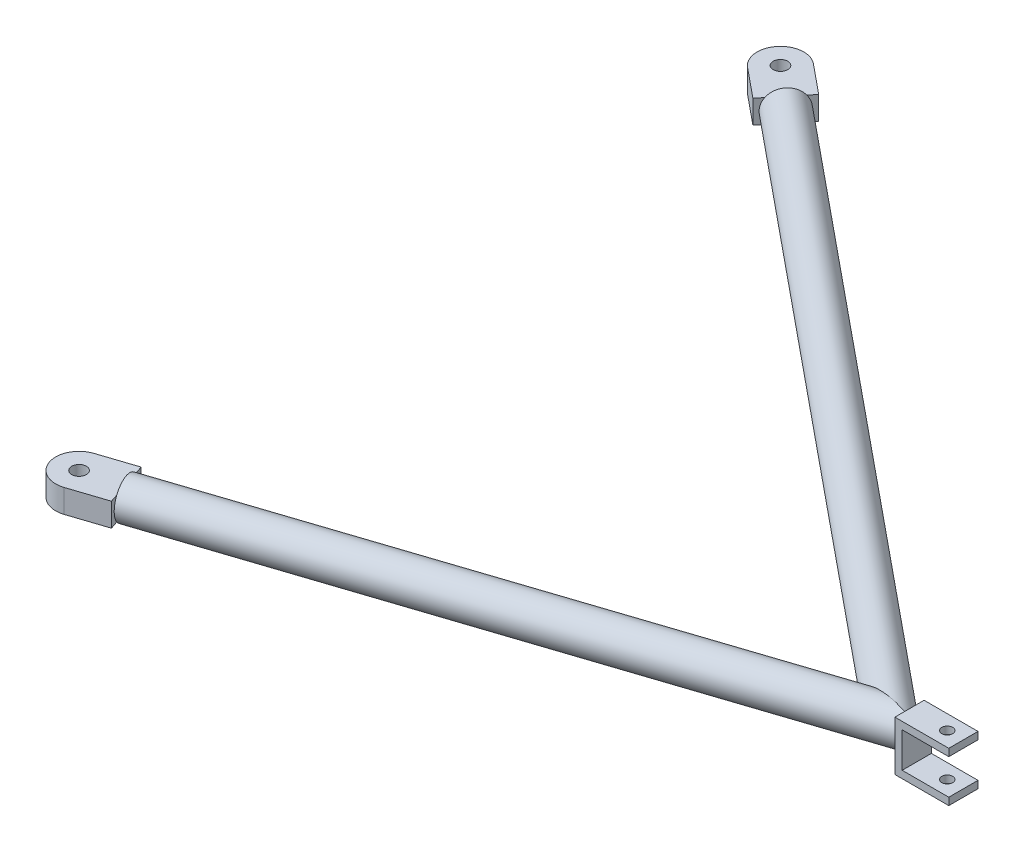
SolidWorks part; units mm, degrees
ref_plane "Front Plane" through (0, 0, 0) normal (0, 0, 1) x (1, 0, 0)
ref_plane "Top Plane" through (0, 0, 0) normal (0, 1, 0) x (1, 0, 0)
ref_plane "Right Plane" through (0, 0, 0) normal (1, 0, 0) x (0, 0, -1)
sketch "Sketch1" plane through (0, 0, 0) normal (0, 1, 0) x (1, 0, 0)
  line L0 (-265.3198, -87.5771) -> (0, 0)
  line L1 (0, 0) -> (-265.3198, 217.2229)
  line L2 (-265.3198, 217.2229) -> (-265.3198, -87.5771) construction
  dimension "D1" = 279.4
  dimension "D2" = 342.9
  dimension "D3" = 304.8
ref_plane "Plane1" through (-265.3198, 0, 87.5771) normal (0.9496, 0, -0.3134) x (-0.3134, 0, -0.9496)
sketch "Sketch2" plane through (-265.3198, 0, 87.5771) normal (0.9496, 0, -0.3134) x (-0.3134, 0, -0.9496)
  circle A0 centre (0, 0) radius 8.255
  dimension "D1" = 16.51
sweep "Sweep1" add profiles "Sketch2" path "Sketch1"
sketch "Sketch3" plane through (0, 0, 0) normal (0, 0, 1) x (1, 0, 0)
  line L0 (33.9318, 10.795) -> (10.504, 10.795)
  line L1 (10.504, 10.795) -> (10.504, -10.795)
  line L2 (10.504, -10.795) -> (33.9318, -10.795)
  line L3 (33.9318, -10.795) -> (33.9318, -7.62)
  line L4 (33.9318, -7.62) -> (13.679, -7.62)
  line L5 (13.679, -7.62) -> (13.679, 7.62)
  line L6 (13.679, 7.62) -> (33.9318, 7.62)
  line L7 (33.9318, 7.62) -> (33.9318, 10.795)
  line L8 (16.854, 0) -> (-16.854, 0) construction
  ellipse E0 centre (0, 0) end of major axis (16.854, 0) minor radius 8.255 construction
  ellipse E1 centre (0, 0) end of major axis (16.854, 0) minor radius 8.255 construction
  point P21 (10.504, 0)
  dimension "D1" = 3.175
  dimension "D2" = 15.24
  dimension "D3" = 3.175
  dimension "D4" = 6.35
extrude "Boss-Extrude1" add sketch "Sketch3" along normal blind 8.89 and the other way blind 3.81
sketch "Sketch4" plane through (-265.3198, 0, 87.5771) normal (-0.9496, 0, 0.3134) x (0.3134, 0, 0.9496)
  line L1 (-10.16, 5.08) -> (10.16, 5.08)
  line L2 (-10.16, 5.08) -> (-10.16, -5.08)
  line L3 (-10.16, -5.08) -> (10.16, -5.08)
  line L4 (10.16, 5.08) -> (10.16, -5.08)
  line L5 (-10.16, 5.08) -> (10.16, -5.08) construction
  line L6 (-10.16, -5.08) -> (10.16, 5.08) construction
  circle A1 centre (0, 0) radius 8.255
  circle A2 centre (0, 0) radius 8.255 construction
  dimension "D2" = 20.32
  dimension "D3" = 10.16
  dimension "D1" = 0
extrude "Boss-Extrude2" add sketch "Sketch4" along normal blind 10.16 and the other way blind 16.256
sketch "Sketch5" plane through (-265.3198, 0, -217.2229) normal (-0.7738, 0, -0.6335) x (-0.6335, 0, 0.7738)
  line L1 (-10.16, 5.08) -> (10.16, 5.08)
  line L2 (-10.16, 5.08) -> (-10.16, -5.08)
  line L3 (-10.16, -5.08) -> (10.16, -5.08)
  line L4 (10.16, 5.08) -> (10.16, -5.08)
  line L5 (-10.16, 5.08) -> (10.16, -5.08) construction
  line L6 (-10.16, -5.08) -> (10.16, 5.08) construction
  point P0 (0, 0)
  dimension "D1" = 20.32
  dimension "D2" = 10.16
extrude "Boss-Extrude3" add sketch "Sketch5" along normal blind 10.16 and the other way blind 16.51
sketch "Sketch6" plane through (0, 5.08, 0) normal (0, 1, 0) x (1, 0, 0)
  line L0 (-246.1089, 214.6254) -> (-266.7449, 231.5205) construction
  line L1 (-258.9814, 198.9027) -> (-279.6174, 215.7978) construction
  line L2 (-279.6174, 215.7978) -> (-266.7449, 231.5205) construction
  line L3 (-271.7561, 209.3616) -> (-279.6174, 215.7978)
  line L4 (-279.6174, 215.7978) -> (-273.1812, 223.6592)
  arc A0 (-273.1812, 223.6592) -> (-271.7561, 209.3616) centre (-265.3198, 217.2229) ccw
extrude "Cut-Extrude1" cut sketch "Sketch6" against normal through all
ref_plane "Plane2" through (0, 0, 0) normal (-0.6335, 0, 0.7738) x (0.7738, 0, 0.6335)
ref_plane "Plane3" through (0, 0, 0) normal (0.3134, 0, 0.9496) x (0.9496, 0, -0.3134)
mirror "Mirror1" about plane through (0, 0, 0) normal (-0.6335, 0, 0.7738) of "Cut-Extrude1"
sketch "Sketch7" plane through (0, 5.08, 0) normal (0, 1, 0) x (1, 0, 0)
  line L0 (-246.6984, -92.1297) -> (-271.7832, -100.4097) construction
  line L1 (-253.0677, -72.8337) -> (-278.1524, -81.1137) construction
  line L2 (-271.7832, -100.4097) -> (-278.1524, -81.1137) construction
  line L3 (-262.1352, -97.2251) -> (-271.7832, -100.4097)
  line L4 (-271.7832, -100.4097) -> (-274.9678, -90.7617)
  arc A0 (-262.1352, -97.2251) -> (-274.9678, -90.7617) centre (-265.3198, -87.5771) cw
extrude "Cut-Extrude2" cut sketch "Sketch7" against normal through all
mirror "Mirror2" about plane through (0, 0, 0) normal (0.3134, 0, 0.9496) of "Cut-Extrude2"
sketch "Sketch8" plane through (-265.3198, 0, 87.5771) normal (-0.9496, 0, 0.3134) x (0.3134, 0, 0.9496)
  line L0 (6.5068, -5.08) -> (-6.5068, -5.08) construction
  line L1 (-6.5068, 5.08) -> (6.5068, 5.08) construction
  line L2 (6.5068, -5.08) -> (-6.5068, -5.08)
  line L3 (-6.5068, 5.08) -> (6.5068, 5.08)
  arc A0 (-6.5068, -5.08) -> (6.5068, -5.08) centre (0, 0) ccw construction
  arc A1 (6.5068, 5.08) -> (-6.5068, 5.08) centre (0, 0) ccw construction
  arc A2 (-6.5068, -5.08) -> (6.5068, -5.08) centre (0, 0) ccw
  arc A3 (6.5068, 5.08) -> (-6.5068, 5.08) centre (0, 0) ccw
extrude "Cut-Extrude3" cut sketch "Sketch8" against normal up to surface (16.256 mm away) up to face at (-247.134, 0, 90.8102)
sketch "Sketch9" plane through (-265.3198, 0, -217.2229) normal (-0.7738, 0, -0.6335) x (-0.6335, 0, 0.7738)
  line L0 (6.5068, -5.08) -> (-6.5068, -5.08) construction
  line L1 (-6.5068, 5.08) -> (6.5068, 5.08) construction
  line L2 (6.5068, -5.08) -> (-6.5068, -5.08)
  line L3 (-6.5068, 5.08) -> (6.5068, 5.08)
  arc A0 (-6.5068, -5.08) -> (6.5068, -5.08) centre (0, 0) ccw construction
  arc A1 (6.5068, 5.08) -> (-6.5068, 5.08) centre (0, 0) ccw construction
  arc A2 (-6.5068, -5.08) -> (6.5068, -5.08) centre (0, 0) ccw
  arc A3 (6.5068, 5.08) -> (-6.5068, 5.08) centre (0, 0) ccw
extrude "Cut-Extrude4" cut sketch "Sketch9" against normal up to surface (16.51 mm away) up to face at (-258.1011, 0, -199.9779)
sketch "Sketch10" plane through (0, 5.08, 0) normal (0, 1, 0) x (1, 0, 0)
  point P0 (-265.3198, 217.2229)
  point P1 (-265.3198, -87.5771)
hole_wizard "E (0.25) Diameter Hole1" positions "3DSketch1" profile "Sketch11" hole size "E" standard "ANSI Inch"
sketch3d "3DSketch1"
  point P0 (-265.3198, 5.08, -217.2229)
  point P3 (-265.3198, 5.08, 87.5771)
sketch "Sketch11" plane through (-265.3198, 5.08, -217.2229) normal (1, 0, 0) x (0, 0, 1)
  line L0 (0, 0) -> (0, 20.9577)
  line L1 (0, 20.9577) -> (3.175, 19.05)
  line L2 (3.175, 19.05) -> (3.175, 0)
  line L5 (3.175, 0) -> (0, 0)
  line L10 (0, 20.9577) -> (-3.175, 19.05) construction
  line L11 (0, -6.35) -> (0, 107.95) construction
  dimension "Hole Dia." = 6.35
  dimension "Hole Depth" = 19.05
  dimension "Drill Angle" = 118
hole_wizard "3/16 (0.1875) Diameter Hole1" positions "Sketch12" profile "Sketch13" hole size "3/16" standard "ANSI Inch" end condition through all
sketch "Sketch12" plane through (0, 10.795, 0) normal (0, 1, 0) x (1, 0, 0)
  point P0 (26.9335, -2.54)
sketch "Sketch13" plane through (26.9335, 10.795, 2.54) normal (1, 0, 0) x (0, 0, 1)
  line L0 (0, 0) -> (0, 21.59)
  line L1 (0, 21.59) -> (2.3812, 21.59)
  line L2 (2.3812, 21.59) -> (2.3812, 0)
  line L5 (2.3812, 0) -> (0, 0)
  line L11 (0, -6.35) -> (0, 107.95) construction
  dimension "Thru Hole Dia." = 4.7625
  dimension "Thru Hole Depth" = 21.59
sketch "Sketch14" plane through (0, 0, 8.89) normal (0, 0, 1) x (1, 0, 0)
  line L1 (13.679, 4.8225) -> (13.679, -4.8225)
  line L2 (13.679, 4.8225) -> (13.679, -4.8225)
  ellipse E1 centre (0, 0) end of major axis (16.854, 0) minor radius 8.255 (13.679, -4.8225) -> (13.679, 4.8225) ccw
  ellipse E2 centre (0, 0) end of major axis (16.854, 0) minor radius 8.255 (13.679, -4.8225) -> (13.679, 4.8225) ccw
  dimension "D1" = 0
extrude "Cut-Extrude5" cut sketch "Sketch14" against normal through all
